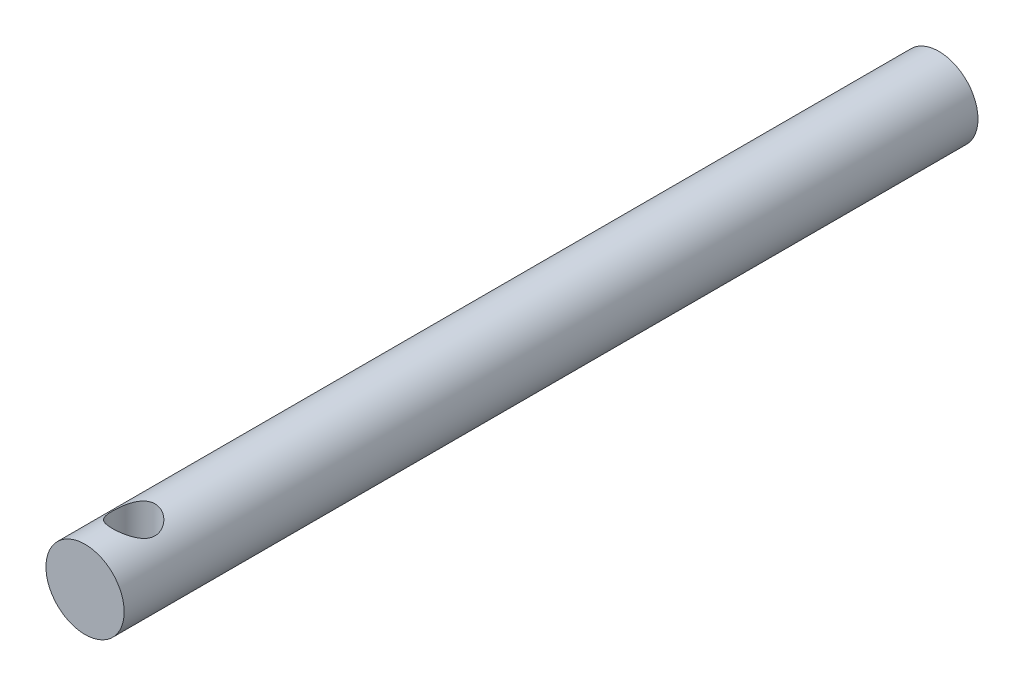
SolidWorks part; units mm, degrees
ref_plane "Plan de face" through (0, 0, 0) normal (0, 0, 1) x (1, 0, 0)
ref_plane "Plan de dessus" through (0, 0, 0) normal (0, 1, 0) x (1, 0, 0)
ref_plane "Plan de droite" through (0, 0, 0) normal (1, 0, 0) x (0, 0, -1)
sketch "Esquisse1" plane through (0, 0, 0) normal (0, 0, 1) x (1, 0, 0)
  circle A0 centre (0, 0) radius 2.75
  dimension "D1" = 5.5
extrude "Boss.-Extru.1" add sketch "Esquisse1" along normal blind 60
sketch "Esquisse3" plane through (0, 0, 0) normal (0, 1, 0) x (1, 0, 0)
  circle A0 centre (0, -56.5833) radius 1.5
  dimension "D1" = 3
extrude "Enlèv. mat.-Extru.1" cut sketch "Esquisse3" against normal blind 3
sketch "Esquisse4" plane through (0, 0, 0) normal (0, -1, 0) x (1, 0, 0)
  circle A0 centre (0, 56.5833) radius 1.5
  dimension "D1" = 3
extrude "Enlèv. mat.-Extru.2" cut sketch "Esquisse4" against normal blind 3
